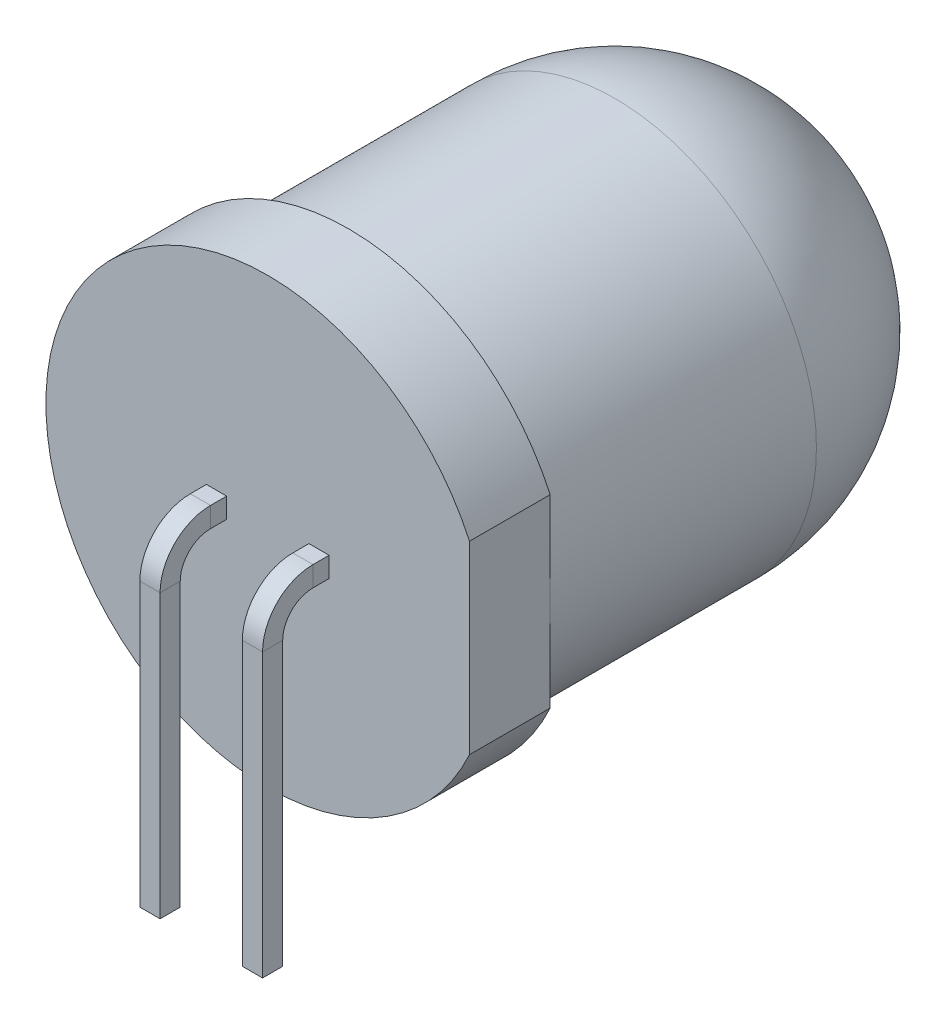
SolidWorks part; units mm, degrees
ref_plane "Front Plane" through (0, 0, 0) normal (0, 0, 1) x (1, 0, 0)
ref_plane "Top Plane" through (0, 0, 0) normal (0, 1, 0) x (1, 0, 0)
ref_plane "Right Plane" through (0, 0, 0) normal (1, 0, 0) x (0, 0, -1)
sketch "Sketch1" plane through (0, 0, 0) normal (0, 1, 0) x (1, 0, 0)
  line L0 (0, 0) -> (0, 13.6)
  line L1 (5, 8.6) -> (5, 2)
  line L2 (5.5, 0) -> (0, 0)
  line L3 (5, 2) -> (5.5, 2)
  line L4 (5.5, 2) -> (5.5, 0)
  arc A0 (0, 13.6) -> (5, 8.6) centre (0, 8.6) cw
  dimension "D1" = 5
  dimension "D2" = 5.5
  dimension "D3" = 2
  dimension "D4" = 13.6
revolve "Revolve1" add sketch "Sketch1" angle 360 about L0
sketch "Sketch2" plane through (0, 0, 0) normal (0, 0, 1) x (1, 0, 0)
  line L1 (5.5, 2.2913) -> (5, 2.2913)
  line L2 (5.5, 2.2913) -> (5.5, -2.2913)
  line L3 (5.5, -2.2913) -> (5, -2.2913)
  line L4 (5, 2.2913) -> (5, -2.2913)
  circle A0 centre (0, 0) radius 5 construction
  circle A1 centre (0, 0) radius 5.5 construction
extrude "Cut-Extrude1" cut sketch "Sketch2" against normal through all
sketch "Sketch3" plane through (0, 0, 0) normal (0, 0, 1) x (1, 0, 0)
  line L0 (0, 1.7562) -> (0, 0) construction
  line L1 (0, 0) -> (1.27, 0) construction
  line L2 (-1.02, 0.25) -> (-1.02, -0.25)
  line L3 (1.02, 0.25) -> (1.52, 0.25)
  line L4 (1.02, 0.25) -> (1.02, -0.25)
  line L5 (1.02, -0.25) -> (1.52, -0.25)
  line L6 (1.52, 0.25) -> (1.52, -0.25)
  line L7 (1.02, 0.25) -> (1.52, -0.25) construction
  line L8 (1.02, -0.25) -> (1.52, 0.25) construction
  line L9 (-1.02, -0.25) -> (-1.52, -0.25)
  line L10 (-1.52, 0.25) -> (-1.52, -0.25)
  line L11 (-1.02, 0.25) -> (-1.52, 0.25)
  dimension "D1" = 0.5
  dimension "D2" = 1.27
ref_plane "Plane1" through (1.27, 0, 0) normal (1, 0, 0) x (0, 0, -1)
sketch "Sketch4" plane through (1.27, 0, 0) normal (1, 0, 0) x (0, 0, -1)
  line L0 (0, 0) -> (-0.4, 0)
  line L1 (-1.4, -1) -> (-1.4, -8)
  arc A0 (-1.4, -1) -> (-0.4, 0) centre (-0.4, -1) cw
  dimension "D3" = 1
  dimension "D1" = 0.4
  dimension "D2" = 8
sweep "Sweep1" add profiles "Sketch3" path "Sketch4"
